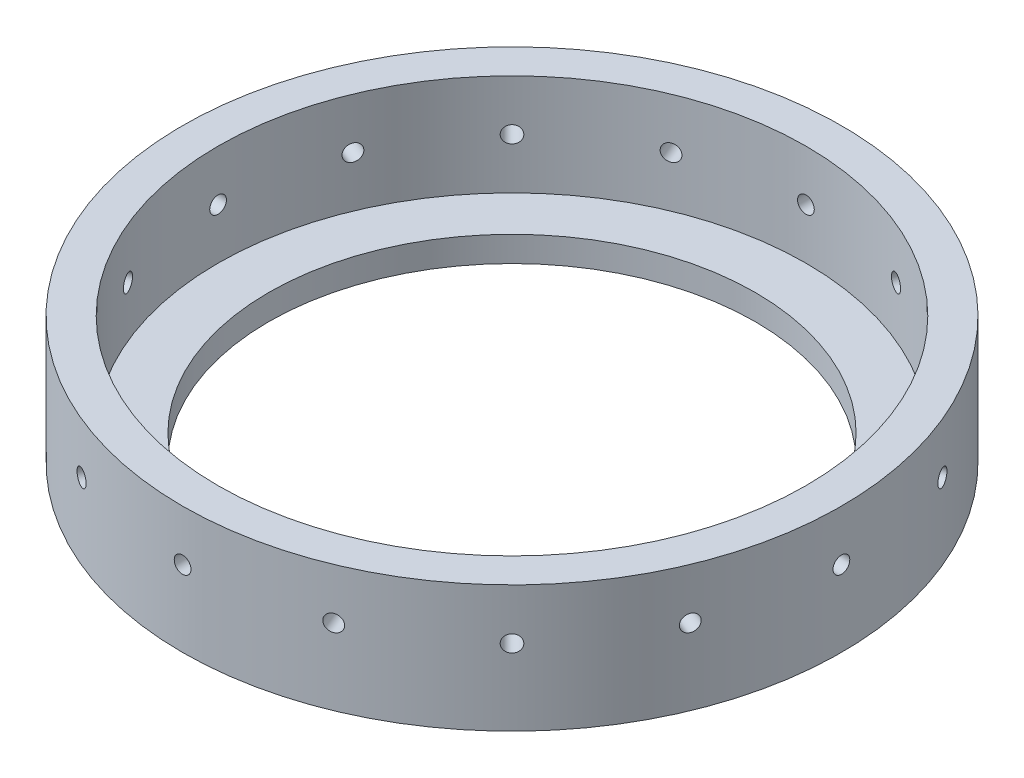
SolidWorks part; units mm, degrees
material "3.1645 (EN AW-2007)"
ref_plane "Płaszczyzna przednia" through (0, 0, 0) normal (0, 0, 1) x (1, 0, 0)
ref_plane "Płaszczyzna górna" through (0, 0, 0) normal (0, 1, 0) x (1, 0, 0)
ref_plane "Płaszczyzna prawa" through (0, 0, 0) normal (1, 0, 0) x (0, 0, -1)
sketch "Szkic2" plane through (0, 0, 0) normal (0, 0, 1) x (1, 0, 0)
  line L0 (48, -12.5) -> (65, -12.5)
  line L1 (65, -12.5) -> (65, 12.5)
  line L2 (65, 12.5) -> (58, 12.5)
  line L3 (58, 12.5) -> (58, -7.5)
  line L4 (58, -7.5) -> (48, -7.5)
  line L5 (48, -7.5) -> (48, -12.5)
  line L6 (0, 61.1808) -> (0, -72.8595) construction
  point P5 (65, 0)
  dimension "D1" = 25
  dimension "D2" = 5
  dimension "D3" = 17
  dimension "D4" = 7
  dimension "D5" = 65
revolve "Obrót1" add sketch "Szkic2" angle 360 about L6
ref_plane "Płaszczyzna1" through (65, 0, 0) normal (1, 0, 0) x (0, 0, -1)
hole_wizard "Otwór gwintowany M4x0.71" positions "Szkic 3D1" profile "Szkic3" tap size "M4x0.7" standard "Ansi Metric"
sketch3d "Szkic 3D1"
  point P0 (65, 2.5, 0)
sketch "Szkic3" plane through (65, 2.5, 0) normal (0, 1, 0) x (0, 0, -1)
  line L0 (0, 0) -> (0, 10)
  line L1 (0, 10) -> (1.65, 9.0086)
  line L2 (1.65, 9.0086) -> (1.65, 0)
  line L5 (1.65, 0) -> (0, 0)
  line L10 (0, 10) -> (-1.65, 9.0086) construction
  line L11 (0, -6.35) -> (0, 107.95) construction
  dimension "Średnica wiertła gwintu" = 3.3
  dimension "Głębokość otworu gwintowanego" = 10
  dimension "Kąt wiertła" = 118
cosmetic thread "Gwint otworu1" parameters "D1"=8, "D2"=4
pattern_circular "Szyk kołowy1" count 16 over 360 about axis through (0, 61.1808, 0) along (0, 1, 0) of "Otwór gwintowany M4x0.71"
cosmetic thread "Gwint otworu2" parameters "D1"=8, "D2"=4
cosmetic thread "Gwint otworu3" parameters "D1"=8, "D2"=4
cosmetic thread "Gwint otworu4" parameters "D1"=8, "D2"=4
cosmetic thread "Gwint otworu5" parameters "D1"=8, "D2"=4
cosmetic thread "Gwint otworu6" parameters "D1"=8, "D2"=4
cosmetic thread "Gwint otworu7" parameters "D1"=8, "D2"=4
cosmetic thread "Gwint otworu8" parameters "D1"=8, "D2"=4
cosmetic thread "Gwint otworu9" parameters "D1"=8, "D2"=4
cosmetic thread "Gwint otworu10" parameters "D1"=8, "D2"=4
cosmetic thread "Gwint otworu11" parameters "D1"=8, "D2"=4
cosmetic thread "Gwint otworu12" parameters "D1"=8, "D2"=4
cosmetic thread "Gwint otworu13" parameters "D1"=8, "D2"=4
cosmetic thread "Gwint otworu14" parameters "D1"=8, "D2"=4
cosmetic thread "Gwint otworu15" parameters "D1"=8, "D2"=4
cosmetic thread "Gwint otworu16" parameters "D1"=8, "D2"=4
